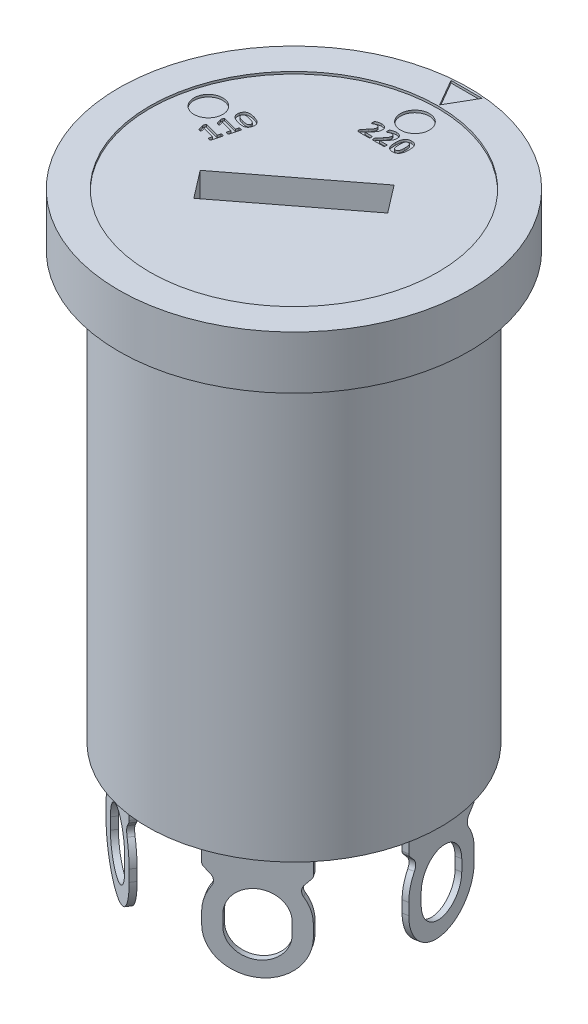
SolidWorks part; units mm, degrees
other "Markup1"
sketch "Sketch8" plane through (7.6, -24.65, 7.6) normal (0.9387, -0.3325, 0.0915) x (-0.3165, -0.936, -0.1541)
ref_plane "Front Plane" through (0, 0, 0) normal (0, 0, 1) x (1, 0, 0)
ref_plane "Top Plane" through (0, 0, 0) normal (0, 1, 0) x (1, 0, 0)
ref_plane "Right Plane" through (0, 0, 0) normal (1, 0, 0) x (0, 0, -1)
sketch "Sketch1" plane through (0, 0, 0) normal (0, 1, 0) x (1, 0, 0)
  circle A0 centre (0, 0) radius 7.6
  dimension "D1" = 15.2
extrude "Boss-Extrude1" add sketch "Sketch1" along normal mid plane 2.3
sketch "Sketch2" plane through (0, -1.15, 0) normal (0, -1, 0) x (1, 0, 0)
  circle A0 centre (0, 0) radius 6.35
  dimension "D1" = 12.7
extrude "Boss-Extrude2" add sketch "Sketch2" along normal blind 18.5
sketch "Sketch3" plane through (0, -19.65, 0) normal (0, -1, 0) x (1, 0, 0)
  line L1 (-5.1372, -2.6828) -> (-4.891, -2.6394)
  line L2 (-5.1372, -2.6828) -> (-5.7449, 0.764)
  line L3 (-5.7449, 0.764) -> (-5.4987, 0.8074)
  line L4 (-4.891, -2.6394) -> (-5.4987, 0.8074)
  line L5 (-5.1372, -2.6828) -> (-5.4987, 0.8074) construction
  line L6 (-5.7449, 0.764) -> (-4.891, -2.6394) construction
  line L11 (-5.318, -0.9377) -> (0, 0) construction
  line L12 (0, 0) -> (0, 6.35) construction
  circle A0 centre (0, 0) radius 6.35 construction
  point P0 (-5.318, -0.9377)
  point P27 (0, 0)
  dimension "D1" = 3.5
  dimension "D2" = 0.25
  dimension "D3" = 5.4
  dimension "D4" = 100
extrude "Boss-Extrude3" add sketch "Sketch3" along normal blind 5 contours L3 L4 L1 L2
sketch "Sketch4" plane through (-5.4411, 0, -0.9594) normal (-0.9848, 0, -0.1736) x (-0.1736, 0, 0.9848)
  line L0 (0, -22.4) -> (0, -22.9) construction
  line L1 (1.0847, -22.4) -> (1.0847, -22.9)
  line L2 (-1.0847, -22.4) -> (-1.0847, -22.9)
  line L3 (1.75, -21.2053) -> (0, -19.65) construction
  line L4 (1.75, -24.65) -> (-1.75, -24.65) construction
  line L5 (0, -22.4) -> (1.75, -21.2053) construction
  line L6 (1.75, -24.65) -> (1.75, -19.65) construction
  line L7 (0, -19.65) -> (0, -24.65) construction
  line L9 (1.75, -19.65) -> (-1.75, -19.65) construction
  line L10 (1.4743, -20.9603) -> (1.75, -20.65)
  line L11 (-6.35, -19.65) -> (6.35, -19.65) construction
  line L12 (0, -22.4) -> (-1.75, -21.2053) construction
  line L13 (-1.75, -21.2053) -> (0, -19.65) construction
  line L14 (-1.4743, -20.9603) -> (-1.75, -20.65)
  arc A0 (1.0847, -22.4) -> (-1.0847, -22.4) centre (0, -22.4) ccw
  arc A1 (-1.0847, -22.9) -> (1.0847, -22.9) centre (0, -22.9) ccw
  arc A2 (1.75, -22.4) -> (1.4453, -21.4133) centre (0, -22.4) ccw
  arc A3 (1.75, -22.9) -> (-1.75, -22.9) centre (0, -22.9) cw
  arc A4 (1.4453, -21.4133) -> (1.4743, -20.9603) centre (1.75, -21.2053) cw
  arc A5 (-1.4453, -21.4133) -> (-1.4743, -20.9603) centre (-1.75, -21.2053) ccw
  arc A6 (-1.75, -22.4) -> (-1.4453, -21.4133) centre (0, -22.4) cw
  point P3 (0, -22.65)
  line M8 (-1.75, -19.65) -> (-1.75, -24.65)
  line M9 (-1.75, -24.65) -> (1.75, -24.65)
  line M10 (1.75, -24.65) -> (1.75, -19.65)
  dimension "D3" = 1
  dimension "D1" = 1.75
  dimension "D2" = 0.5
extrude "Cut-Extrude1" cut sketch "Sketch4" against normal up to next contours L2 A1 L1 A0 | A4 A2 L10 M10 | A6 A5 L14 M8 | A3 M9 M8 | A3 M10 M9
fillet "Fillet1" radius 0.2 2 edges at (-5.0141, -20.65, -2.6611) (-5.6218, -20.65, 0.7857)
pattern_circular "CirPattern1" count 4 every 66.667 about axis through (0, 0, 0) along (0, 1, 0) of "Boss-Extrude3", "Cut-Extrude1", "Fillet1"
sketch "Sketch5" plane through (0, 1.15, 0) normal (0, 1, 0) x (1, 0, 0)
  line L1 (0, 6.3206) -> (0.675, 7.4897)
  line L2 (0.675, 7.4897) -> (-0.675, 7.4897)
  line L3 (-0.675, 7.4897) -> (0, 6.3206)
  circle A0 centre (0, 0) radius 6.25
  circle A1 centre (0, 7.1) radius 0.3897 construction
  dimension "D1" = 12.5
  dimension "D2" = 7.1
  dimension "D3" = 1.35
extrude "Cut-Extrude2" cut sketch "Sketch5" against normal blind 0.1
sketch "Sketch6" plane through (0, 1.05, 0) normal (0, 1, 0) x (1, 0, 0)
  line L0 (0, 0) -> (6.25, 0) construction
  line L1 (-2.8366, -1.2313) -> (1.9235, 2.4213)
  line L2 (-2.8366, -1.2313) -> (-1.9235, -2.4213)
  line L3 (-1.9235, -2.4213) -> (2.8366, 1.2313)
  line L4 (1.9235, 2.4213) -> (2.8366, 1.2313)
  line L5 (-2.8366, -1.2313) -> (2.8366, 1.2313) construction
  line L6 (-1.9235, -2.4213) -> (1.9235, 2.4213) construction
  circle A0 centre (0, 0) radius 6.25 construction
  point P0 (0, 0)
  dimension "D1" = 6
  dimension "D2" = 1.5
  dimension "D3" = 37.5
extrude "Cut-Extrude3" cut sketch "Sketch6" against normal blind 3
sketch "Sketch7" plane through (0, 1.05, 0) normal (0, 1, 0) x (1, 0, 0)
  line L0 (-5.0711, 1.3588) -> (0, 0) construction
  line L1 (0, 0) -> (0, 5.25) construction
  line L2 (-1.5, 3.65) -> (1.5, 3.65) construction
  line L3 (-3.1374, 2.3936) -> (-3.9139, -0.5042) construction
  circle A1 centre (0, 5.25) radius 0.625
  circle A2 centre (-5.0711, 1.3588) radius 0.625
  circle A3 centre (0, 0) radius 5.25 construction
  text T0 "110" font "Calibri" height in points 3
  text T1 "220" font "Calibri" height in points 3
  point P13 (0, 3.65)
  point P14 (-3.5256, 0.9447)
  dimension "D1" = 1.25
  dimension "D2" = 1.25
  dimension "D3" = 10.5
  dimension "D4" = 75
  dimension "D5" = 1.6
  dimension "D6" = 3
  dimension "D7" = 3
  dimension "D8" = 1.6
extrude "Cut-Extrude4" cut sketch "Sketch7" against normal blind 0.1
